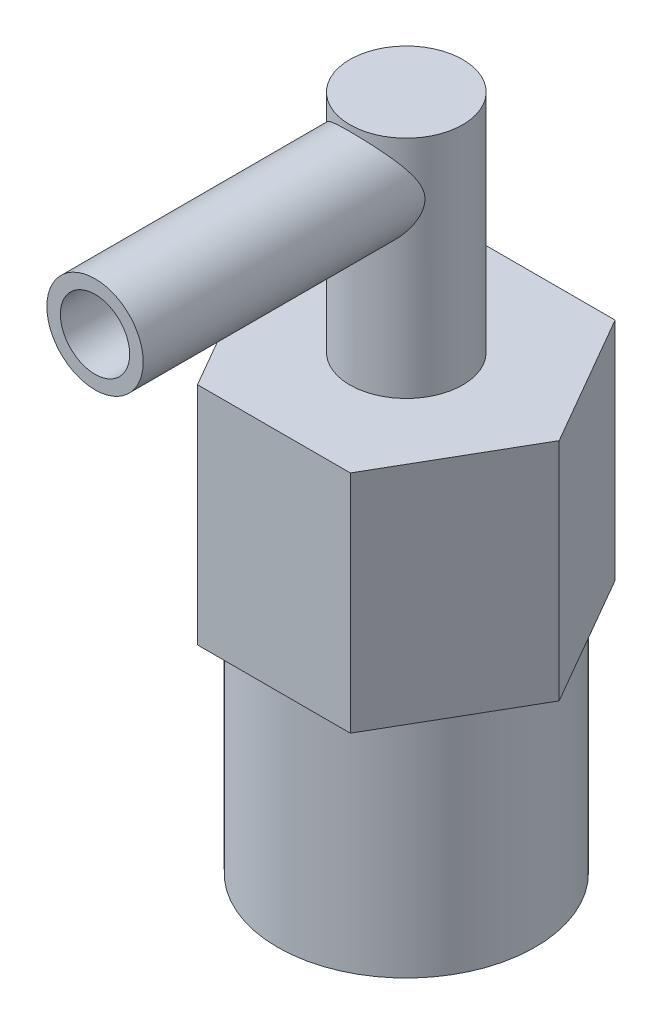
SolidWorks part; units mm, degrees
ref_plane "Front Plane" through (0, 0, 0) normal (0, 0, 1) x (1, 0, 0)
ref_plane "Top Plane" through (0, 0, 0) normal (0, 1, 0) x (1, 0, 0)
ref_plane "Right Plane" through (0, 0, 0) normal (1, 0, 0) x (0, 0, -1)
sketch "Sketch1" plane through (0, 0, 0) normal (0, 1, 0) x (1, 0, 0)
  circle A0 centre (0, 0) radius 4.7625
  circle A1 centre (0, 0) radius 3.175
  dimension "D1" = 9.525
extrude "Boss-Extrude1" add sketch "Sketch1" along normal blind 8.3312
sketch "Sketch2" plane through (0, 8.3312, 0) normal (0, 1, 0) x (1, 0, 0)
  line L1 (5.6506, 0) -> (2.8253, 4.8936)
  line L2 (2.8253, 4.8936) -> (-2.8253, 4.8936)
  line L3 (-2.8253, 4.8936) -> (-5.6506, 0)
  line L4 (-5.6506, 0) -> (-2.8253, -4.8936)
  line L5 (-2.8253, -4.8936) -> (2.8253, -4.8936)
  line L6 (2.8253, -4.8936) -> (5.6506, 0)
  circle A0 centre (0, 0) radius 4.8936 construction
extrude "Boss-Extrude2" add sketch "Sketch2" along normal blind 8.3312
sketch "Sketch3" plane through (0, 16.6624, 0) normal (0, 1, 0) x (1, 0, 0)
  circle A0 centre (0, 0) radius 1.5875
  circle A1 centre (0, 0) radius 2.0875
  dimension "D1" = 3.175
  dimension "D2" = 0.5
extrude "Boss-Extrude3" add sketch "Sketch3" along normal blind 8.3312
sketch "Sketch4" plane through (0, 24.9936, 0) normal (0, 1, 0) x (1, 0, 0)
  circle A0 centre (0, 0) radius 2.0875
extrude "Boss-Extrude4" add sketch "Sketch4" along normal blind 0.001
ref_plane "Plane1" through (0, 0, 0) normal (0, 0, 1) x (1, 0, 0)
sketch "Sketch5" plane through (0, 0, 0) normal (0, 0, 1) x (1, 0, 0)
  line L0 (0, 24.9946) -> (0, 22.9946) construction
  line L1 (2.0875, 24.9946) -> (-2.0875, 24.9946) construction
  circle A0 centre (0, 22.9946) radius 1.78
  circle A1 centre (0, 22.9946) radius 1.28
  dimension "D1" = 2
  dimension "D2" = 0.5
extrude "Boss-Extrude5" add sketch "Sketch5" along normal blind 11.5062
